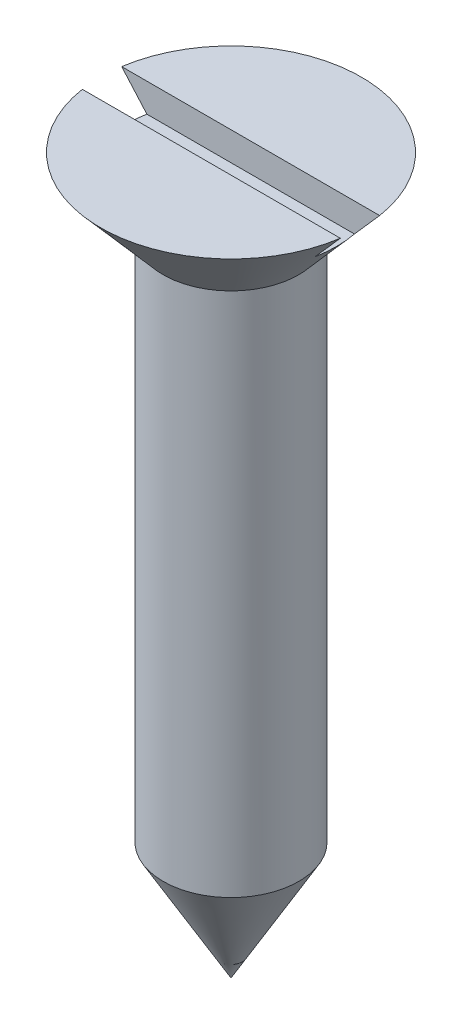
SolidWorks part; units mm, degrees
ref_plane "Front Plane" through (0, 0, 0) normal (0, 0, 1) x (1, 0, 0)
ref_plane "Top Plane" through (0, 0, 0) normal (0, 1, 0) x (1, 0, 0)
ref_plane "Right Plane" through (0, 0, 0) normal (1, 0, 0) x (0, 0, -1)
sketch "Sketch2" plane through (0, 0, 0) normal (0, 1, 0) x (1, 0, 0)
  circle A0 centre (0, 0) radius 2.413
  dimension "D1" = 4.826
extrude "Boss-Extrude2" add sketch "Sketch2" along normal blind 25.4
sketch "Sketch3" plane through (0, 0, 0) normal (0, 0, 1) x (1, 0, 0)
  line L0 (0, 25.4) -> (0, 20.0675)
  line L1 (2.413, 25.4) -> (-2.413, 25.4) construction
  line L2 (0, 20.0675) -> (4.6355, 25.4)
  line L3 (4.6355, 25.4) -> (0, 25.4)
  line L4 (0, 20.0675) -> (0, 28.0105) construction
  dimension "D1" = 41
  dimension "D2" = 9.271
revolve "Revolve1" add sketch "Sketch3" angle 360 about L4
sketch "Sketch4" plane through (0, 0, 0) normal (1, 0, 0) x (0, 0, -1)
  line L0 (0, 2.7142) -> (0, -0.635) construction
  line L1 (0, -0.635) -> (0, 0)
  line L2 (0, 0) -> (2.413, 4.1794)
  line L3 (2.413, 0) -> (2.413, 22.8433) construction
  line L4 (2.413, 4.1794) -> (2.413, -0.635)
  line L5 (2.413, -0.635) -> (0, -0.635)
  dimension "D1" = 30
  dimension "D2" = 0.635
revolve "Cut-Revolve1" cut sketch "Sketch4" angle 360 about L0
sketch "Sketch5" plane through (0, 25.4, 0) normal (0, 1, 0) x (1, 0, 0)
  line L0 (-4.6355, 0) -> (-4.6355, 2.1021) construction
  line L1 (-5.9055, -0.6985) -> (5.9055, -0.6985)
  line L2 (-5.9055, -0.6985) -> (-5.9055, 0.6985)
  line L3 (-5.9055, 0.6985) -> (5.9055, 0.6985)
  line L4 (5.9055, -0.6985) -> (5.9055, 0.6985)
  line L5 (-5.9055, -0.6985) -> (5.9055, 0.6985) construction
  line L6 (-5.9055, 0.6985) -> (5.9055, -0.6985) construction
  circle A0 centre (0, 0) radius 4.6355 construction
  point P0 (0, 0)
  dimension "D1" = 1.27
  dimension "D2" = 1.397
extrude "Cut-Extrude1" cut sketch "Sketch5" against normal blind 1.016
